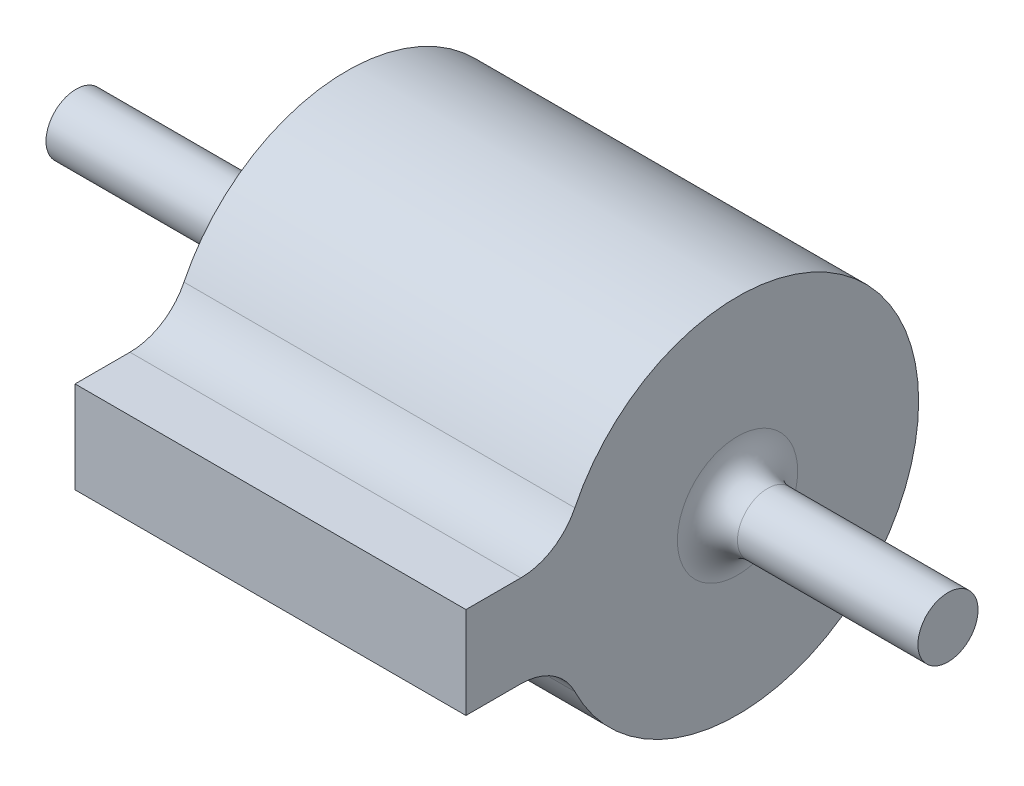
SolidWorks part; units mm, degrees
material "AISI 1020"
ref_plane "Front Plane" through (0, 0, 0) normal (0, 0, 1) x (1, 0, 0)
ref_plane "Top Plane" through (0, 0, 0) normal (0, 1, 0) x (1, 0, 0)
ref_plane "Right Plane" through (0, 0, 0) normal (1, 0, 0) x (0, 0, -1)
sketch "Sketch1" plane through (0, 0, 0) normal (1, 0, 0) x (0, 0, -1)
  line L0 (-58.2779, 15.2606) -> (-90.3314, 15.2606)
  line L1 (-90.3314, 15.2606) -> (-90.3314, -15.2606)
  line L2 (-90.3314, -15.2606) -> (-58.2779, -15.2606)
  arc A0 (-58.2779, -15.2606) -> (-58.2779, 15.2606) centre (0, 0) ccw
  arc A1 (-9.5394, -3) -> (-9.5394, 3) centre (0, 0) ccw
  arc A2 (-9.5394, 3) -> (-9.5394, -3) centre (0, 0) ccw
  point P9 (-90.3314, 0)
  dimension "D1" = 10
extrude "Boss-Extrude1" add sketch "Sketch1" along normal blind 130
fillet "Fillet1" radius 20 2 edges at (65, -15.2606, 58.2779) (65, 15.2606, 58.2779)
sketch "Sketch2" plane through (0, 0, 0) normal (-1, 0, 0) x (0, 0, 1)
  circle A0 centre (0, 0) radius 10
  dimension "D1" = 20
extrude "Boss-Extrude2" add sketch "Sketch2" along normal blind 90 and the other way blind 200
fillet "Fillet2" radius 10 2 edges at (0, 0, -10) (130, 0, -10)
